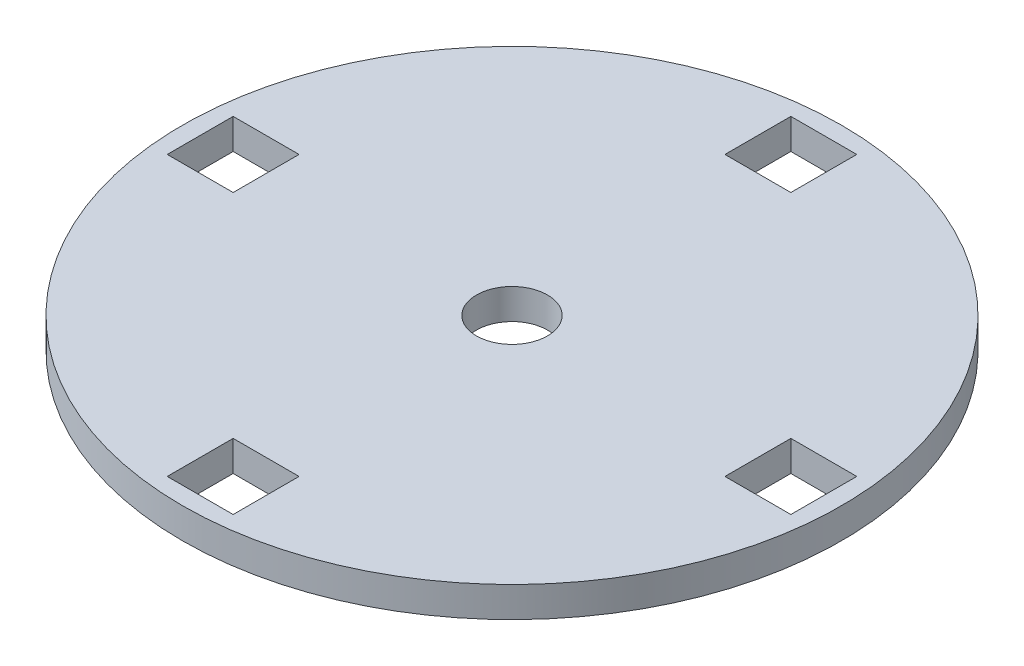
SolidWorks part; units mm, degrees
material "Mahogany"
ref_plane "Front Plane" through (0, 0, 0) normal (0, 0, 1) x (1, 0, 0)
ref_plane "Top Plane" through (0, 0, 0) normal (0, 1, 0) x (1, 0, 0)
ref_plane "Right Plane" through (0, 0, 0) normal (1, 0, 0) x (0, 0, -1)
sketch "Sketch1" plane through (0, 0, 0) normal (0, 1, 0) x (1, 0, 0)
  circle A0 centre (0, 0) radius 32.5
  dimension "D1" = 65
extrude "Boss-Extrude1" add sketch "Sketch1" along normal blind 3
sketch "Sketch2" plane through (0, 0, 0) normal (0, 1, 0) x (1, 0, 0)
  line L5 (3.25, -30.75) -> (-3.25, -30.75)
  line L6 (24.25, 3.25) -> (30.75, 3.25)
  line L18 (24.25, 3.25) -> (24.25, -3.25)
  line L19 (24.25, -3.25) -> (30.75, -3.25)
  line L20 (30.75, 3.25) -> (30.75, -3.25)
  line L21 (24.25, 3.25) -> (30.75, -3.25) construction
  line L22 (24.25, -3.25) -> (30.75, 3.25) construction
  line L23 (3.25, -24.25) -> (3.25, -30.75)
  line L24 (3.25, -24.25) -> (-3.25, -24.25)
  line L25 (-3.25, -24.25) -> (-3.25, -30.75)
  line L26 (-30.75, -3.25) -> (-30.75, 3.25)
  line L27 (-24.25, -3.25) -> (-30.75, -3.25)
  line L28 (-24.25, -3.25) -> (-24.25, 3.25)
  line L29 (-24.25, 3.25) -> (-30.75, 3.25)
  line L30 (-3.25, 30.75) -> (3.25, 30.75)
  line L31 (-3.25, 24.25) -> (-3.25, 30.75)
  line L32 (-3.25, 24.25) -> (3.25, 24.25)
  line L33 (3.25, 24.25) -> (3.25, 30.75)
  line L34 (-3.25, 30.75) -> (3.25, 24.25) construction
  line L35 (3.25, 30.75) -> (-3.25, 24.25) construction
  line L36 (-3.25, -24.25) -> (3.25, -30.75) construction
  line L37 (3.25, -24.25) -> (-3.25, -30.75) construction
  circle A0 centre (0, 0) radius 27.5 construction
  circle A1 centre (0, 0) radius 27.5 construction
  circle A2 centre (0, 0) radius 27.5 construction
  circle A3 centre (0, 0) radius 27.5 construction
  circle A4 centre (0, 0) radius 3.5
  point P3 (27.5, 0)
  point P23 (0, 0)
  point P27 (0, 0)
  dimension "D1" = 55
  dimension "D2" = 6.5
  dimension "D5" = 7
  dimension "D3" = 4
  dimension "D4" = 6.5
extrude "Cut-Extrude1" cut sketch "Sketch2" along normal blind 10 and the other way through all
